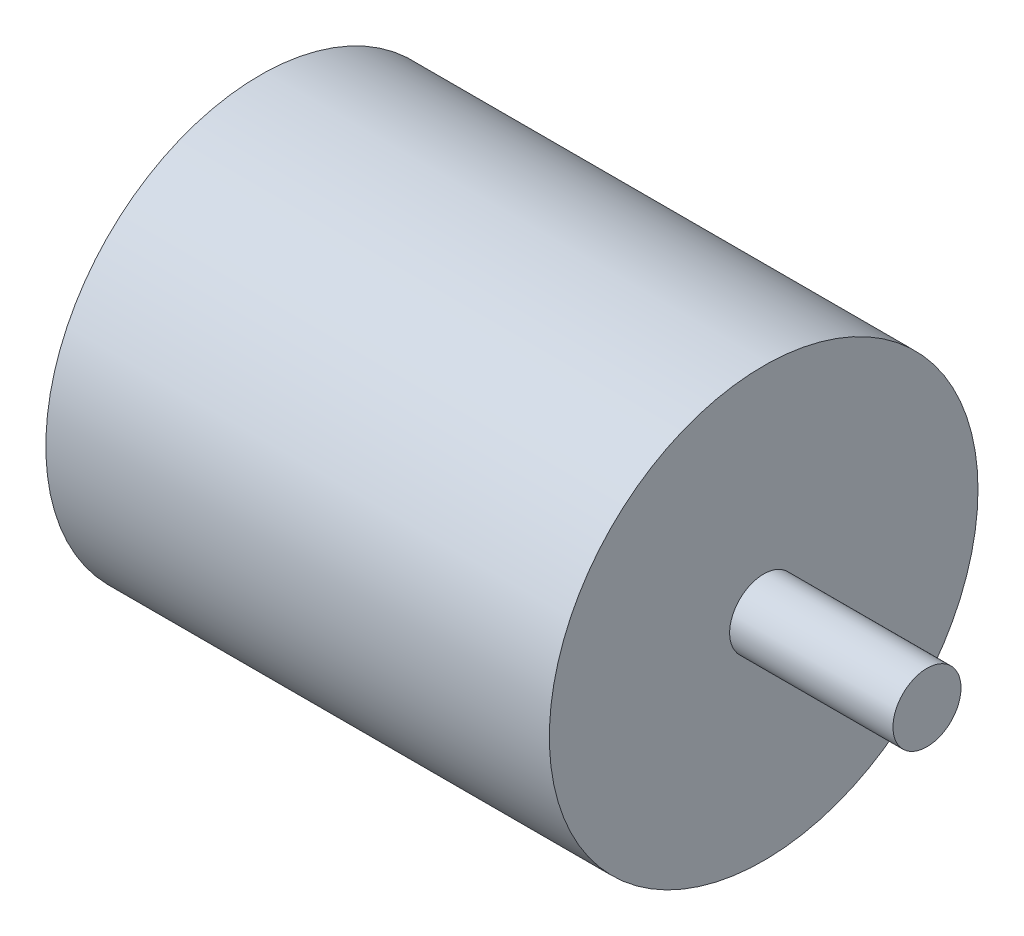
SolidWorks part; units mm, degrees
ref_plane "Front Plane" through (0, 0, 0) normal (0, 0, 1) x (1, 0, 0)
ref_plane "Top Plane" through (0, 0, 0) normal (0, 1, 0) x (1, 0, 0)
ref_plane "Right Plane" through (0, 0, 0) normal (1, 0, 0) x (0, 0, -1)
sketch "Sketch1" plane through (0, 0, 0) normal (1, 0, 0) x (0, 0, -1)
  circle A0 centre (0, 0) radius 31.5
  dimension "D1" = 63
extrude "Boss-Extrude1" add sketch "Sketch1" along normal blind 74
sketch "Sketch4" plane through (74, 0, 0) normal (1, 0, 0) x (0, 0, -1)
  circle A0 centre (0, 0) radius 5
  dimension "D1" = 10
extrude "Boss-Extrude3" add sketch "Sketch4" along normal blind 24
